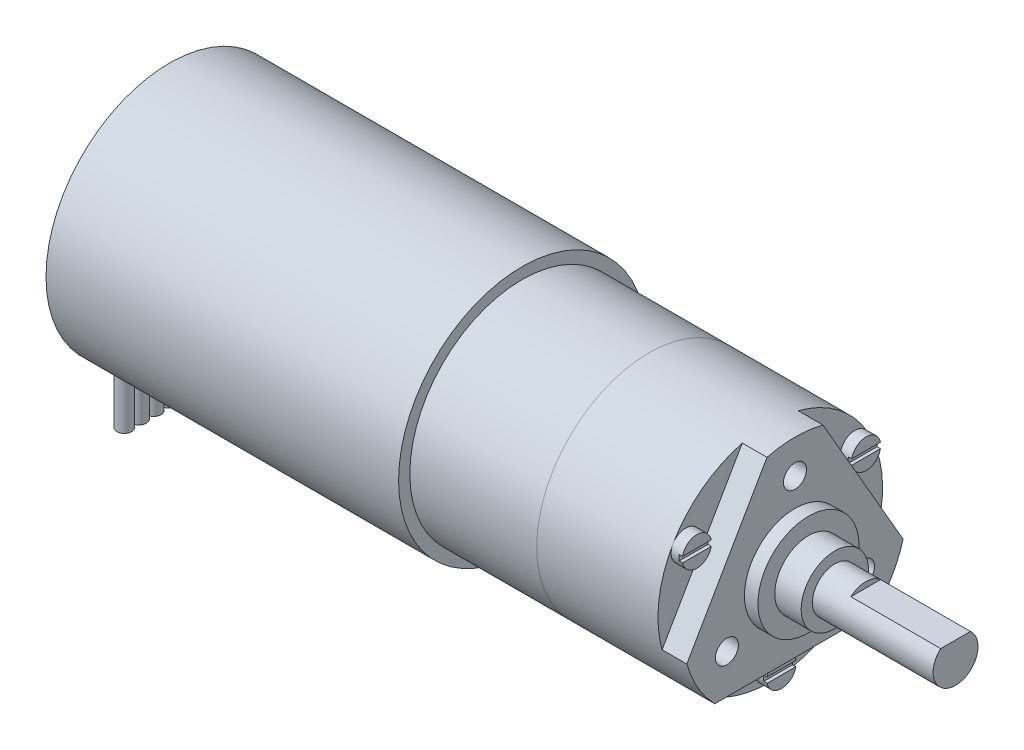
SolidWorks part; units mm, degrees
material "1.4301 (X5CrNi18-10)"
ref_plane "Face" through (0, 0, 0) normal (0, 0, 1) x (1, 0, 0)
ref_plane "Dessus" through (0, 0, 0) normal (0, 1, 0) x (1, 0, 0)
ref_plane "Droite" through (0, 0, 0) normal (1, 0, 0) x (0, 0, -1)
sketch "Esquisse1" plane through (0, 0, 0) normal (0, 0, 1) x (1, 0, 0)
  line L0 (0, 0) -> (70, 0) construction
  line L1 (70, 0) -> (70, 2)
  line L2 (70, 2) -> (59.25, 2)
  line L3 (59.25, 2) -> (59.25, 3)
  line L4 (59.25, 3) -> (56.9, 3)
  line L5 (56.9, 3) -> (56.9, 4.5)
  line L6 (56.9, 4.5) -> (55.7, 4.5)
  line L7 (55.7, 4.5) -> (55.7, 10)
  line L8 (55.7, 10) -> (31.4, 10)
  line L9 (31.4, 10) -> (31.4, 11)
  line L10 (31.4, 11) -> (0, 11)
  line L11 (0, 11) -> (0, 0)
  line L12 (0, 0) -> (70, 0)
  dimension "D1" = 4
  dimension "D2" = 10.75
  dimension "D3" = 6
  dimension "D4" = 9
  dimension "D5" = 20
  dimension "D6" = 22
  dimension "D7" = 14.3
  dimension "D8" = 1.2
  dimension "D9" = 24.3
  dimension "D10" = 55.7
revolve "Révolution1" add sketch "Esquisse1" angle 360 about L0
hole_wizard "Trou taraudé M2.51" positions "Esquisse3" profile "Esquisse2" tap size "M2.5" standard "Iso"
sketch "Esquisse3" plane through (55.7, 0, 0) normal (1, 0, 0) x (0, 0, -1)
  line L0 (0, 7) -> (-6.0622, -3.5) construction
  line L1 (-6.0622, -3.5) -> (6.0622, -3.5) construction
  line L2 (6.0622, -3.5) -> (0, 7) construction
  circle A0 centre (0, 0) radius 7
  point P0 (0, 7)
  point P8 (-6.0622, -3.5)
  point P9 (6.0622, -3.5)
  dimension "D1" = 14
sketch "Esquisse2" plane through (55.7, 7, 0) normal (0, 1, 0) x (0, 0, -1)
  line L0 (0, 0) -> (0, 4.9659)
  line L1 (0, 4.9659) -> (1.025, 4.35)
  line L2 (1.025, 4.35) -> (1.025, 0)
  line L5 (1.025, 0) -> (0, 0)
  line L10 (0, 4.9659) -> (-1.025, 4.35) construction
  line L11 (0, -6.35) -> (0, 107.95) construction
  dimension "Diamètre du trou pour taraudage" = 2.05
  dimension "Profondeur du trou pour taraudage" = 4.35
  dimension "Angle de pointe" = 118
cosmetic thread "Filetage de perçage1" parameters "D1"=3, "D2"=2.5
cosmetic thread "Filetage de perçage2" parameters "D1"=3, "D2"=2.5
cosmetic thread "Filetage de perçage3" parameters "D1"=3, "D2"=2.5
sketch "Esquisse4" plane through (55.7, 0, 0) normal (1, 0, 0) x (0, 0, -1)
  line L0 (0, 14) -> (-12.1244, -7)
  line L1 (-12.1244, -7) -> (12.1244, -7)
  line L2 (12.1244, -7) -> (0, 14)
  line L3 (0, -7) -> (0, -10) construction
  circle A0 centre (0, 0) radius 10 construction
  circle A1 centre (0, 0) radius 10
  circle A2 centre (0, 0) radius 14
  circle M4 centre (0, 0) radius 10
  dimension "D1" = 3
extrude "Enlèv. mat.-Extru.1" cut sketch "Esquisse4" against normal blind 2.2 contours L0 M4 | L3 L1 M4 | L1 L3 A1 | L2 M4
sketch "Esquisse5" plane through (53.5, 0, 0) normal (1, 0, 0) x (0, 0, -1)
  line L0 (0, -8.7) -> (-7.5344, 4.35) construction
  line L1 (-7.5344, 4.35) -> (7.5344, 4.35) construction
  line L2 (7.5344, 4.35) -> (0, -8.7) construction
  circle A0 centre (0, 0) radius 8.7 construction
  circle A1 centre (-7.5344, 4.35) radius 1.3
  circle A2 centre (7.5344, 4.35) radius 1.3
  circle A3 centre (0, -8.7) radius 1.3
  circle A4 centre (0, 0) radius 10 construction
  circle A5 centre (0, 0) radius 10 construction
  dimension "D1" = 2.6
extrude "Boss.-Extru.1" add sketch "Esquisse5" along normal blind 1
sketch "Esquisse6" plane through (54.5, 0, 0) normal (1, 0, 0) x (0, 0, -1)
  line L1 (-6.2344, 4.1) -> (-8.8344, 4.1)
  line L2 (-6.2344, 4.1) -> (-6.2344, 4.6)
  line L3 (-6.2344, 4.6) -> (-8.8344, 4.6)
  line L4 (-8.8344, 4.1) -> (-8.8344, 4.6)
  line L5 (-6.2344, 4.1) -> (-8.8344, 4.6) construction
  line L6 (-6.2344, 4.6) -> (-8.8344, 4.1) construction
  line L7 (8.8344, 4.1) -> (6.2344, 4.1)
  line L8 (8.8344, 4.1) -> (8.8344, 4.6)
  line L9 (8.8344, 4.6) -> (6.2344, 4.6)
  line L10 (6.2344, 4.1) -> (6.2344, 4.6)
  line L11 (8.8344, 4.1) -> (6.2344, 4.6) construction
  line L12 (8.8344, 4.6) -> (6.2344, 4.1) construction
  line L13 (1.3, -8.95) -> (-1.3, -8.95)
  line L14 (1.3, -8.95) -> (1.3, -8.45)
  line L15 (1.3, -8.45) -> (-1.3, -8.45)
  line L16 (-1.3, -8.95) -> (-1.3, -8.45)
  line L17 (1.3, -8.95) -> (-1.3, -8.45) construction
  line L18 (1.3, -8.45) -> (-1.3, -8.95) construction
  circle A4 centre (-7.5344, 4.35) radius 1.3 construction
  point P0 (-7.5344, 4.35)
  point P8 (7.5344, 4.35)
  point P14 (0, -8.7)
  dimension "D1" = 0.5
extrude "Enlèv. mat.-Extru.2" cut sketch "Esquisse6" against normal blind 0.3
sketch "Esquisse7" plane through (0, 0, 0) normal (0, 0, 1) x (1, 0, 0)
  line L0 (70, -2) -> (70, 2) construction
  line L1 (70, 2) -> (62, 2)
  line L2 (70, 2) -> (70, 1.5)
  line L3 (70, 1.5) -> (62, 1.5)
  line L4 (62, 2) -> (62, 1.5)
  dimension "D1" = 8
  dimension "D2" = 3.5
extrude "Enlèv. mat.-Extru.3" cut sketch "Esquisse7" against normal through all and the other way through all
sketch "Esquisse8" plane through (0, 0, 0) normal (-1, 0, 0) x (0, 0, 1)
  line L0 (-4.613, -5.85) -> (4.613, -5.85)
  line L1 (0, 7.45) -> (0, -5.85) construction
  arc A0 (4.613, -5.85) -> (-4.613, -5.85) centre (0, 0) ccw
  dimension "D1" = 7.45
  dimension "D2" = 13.3
extrude "Boss.-Extru.2" add sketch "Esquisse8" along normal blind 2.4
sketch "Esquisse9" plane through (0, -5.85, 0) normal (0, -1, 0) x (1, 0, 0)
  line L0 (-0.75, 3.275) -> (-0.75, 1.965) construction
  line L1 (-0.75, 1.965) -> (-0.75, 0.655) construction
  line L2 (-0.75, 0.655) -> (-0.75, -0.655) construction
  line L3 (-0.75, -0.655) -> (-0.75, -1.965) construction
  line L4 (-0.75, -1.965) -> (-0.75, -3.275) construction
  line L5 (-0.75, 0) -> (0, 0) construction
  line L6 (0, 11) -> (0, -11) construction
  circle A0 centre (-0.75, 3.275) radius 0.65
  circle A1 centre (-0.75, 1.965) radius 0.65
  circle A2 centre (-0.75, 0.655) radius 0.65
  circle A3 centre (-0.75, -0.655) radius 0.65
  circle A4 centre (-0.75, -1.965) radius 0.65
  circle A5 centre (-0.75, -3.275) radius 0.65
  dimension "D2" = 1.3
  dimension "D1" = 1.31
  dimension "D3" = 0.75
extrude "Boss.-Extru.3" add sketch "Esquisse9" along normal blind 10
ref_plane "Plan1" through (42.7, 0, 0) normal (1, 0, 0) x (0, 0, -1)
split line "Ligne de séparation1"
